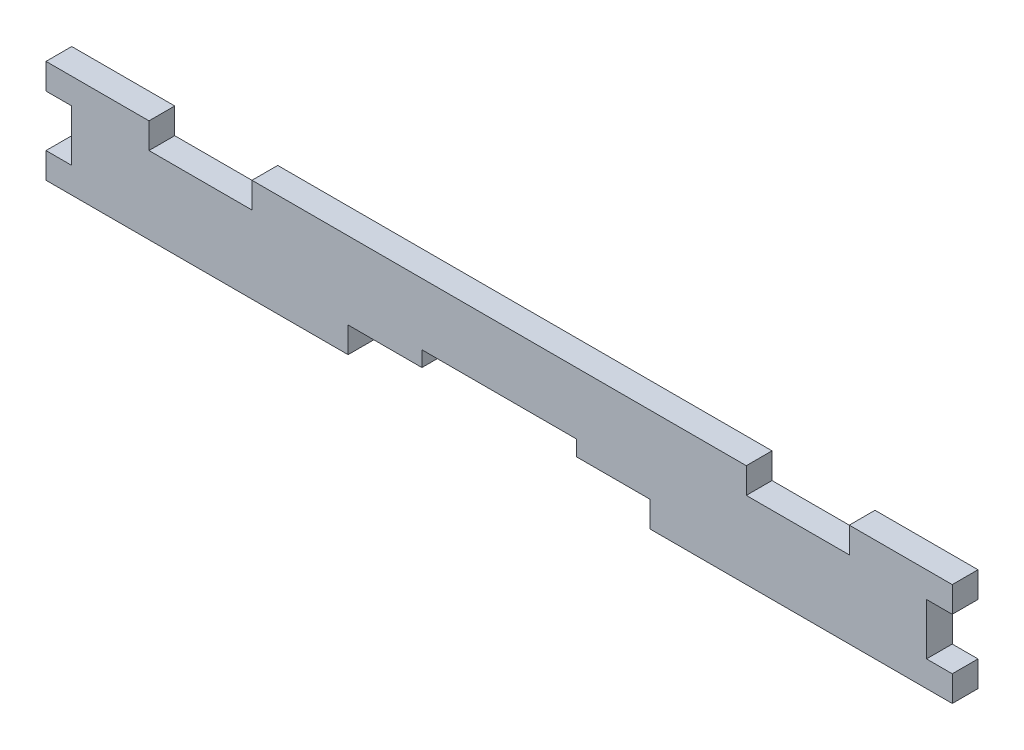
SolidWorks part; units mm, degrees
ref_plane "Alzado" through (0, 0, 0) normal (0, 0, 1) x (1, 0, 0)
ref_plane "Planta" through (0, 0, 0) normal (0, 1, 0) x (1, 0, 0)
ref_plane "Vista lateral" through (0, 0, 0) normal (1, 0, 0) x (0, 0, -1)
sketch "Croquis1" plane through (0, 0, 0) normal (0, 0, 1) x (1, 0, 0)
  line L0 (117.3333, 0) -> (176, 0)
  line L1 (0, 0) -> (58.6667, 0)
  line L2 (0, 0) -> (0, 5)
  line L3 (0, 20) -> (20, 20)
  line L4 (176, 0) -> (176, 5)
  line L6 (58.6667, 0) -> (58.6667, 5)
  line L7 (58.6667, 5) -> (117.3333, 5)
  line L8 (117.3333, 0) -> (117.3333, 5)
  line L9 (88, 15) -> (88, 10) construction
  line L10 (0, 15) -> (5, 15)
  line L12 (0, 5) -> (5, 5)
  line L13 (5, 15) -> (5, 5)
  line L14 (0, 15) -> (0, 20)
  line L15 (176, 15) -> (171, 15)
  line L16 (171, 15) -> (171, 5)
  line L17 (176, 5) -> (171, 5)
  line L18 (176, 15) -> (176, 20)
  line L19 (136, 20) -> (136, 15)
  line L25 (20, 20) -> (20, 15)
  line L26 (20, 15) -> (40, 15)
  line L27 (40, 20) -> (40, 15)
  line L28 (156, 15) -> (136, 15)
  line L29 (156, 20) -> (156, 15)
  line L30 (40, 20) -> (136, 20)
  line L31 (156, 20) -> (176, 20)
  dimension "D1" = 176
  dimension "D2" = 20
  dimension "D3" = 58.6667
  dimension "D4" = 58.6667
  dimension "D5" = 5
  dimension "D6" = 10
  dimension "D7" = 5
  dimension "D8" = 5
  dimension "D9" = 5
  dimension "D10" = 20
  dimension "D11" = 20
extrude "Saliente-Extruir1" add sketch "Croquis1" along normal blind 5
sketch "Croquis2" plane through (0, 0, 5) normal (0, 0, 1) x (1, 0, 0)
  line L0 (58.6667, 5) -> (117.3333, 5) construction
  line L5 (73.0017, 5) -> (103.0017, 5)
  line L6 (73.0017, 5) -> (73.0017, 8)
  line L7 (73.0017, 8) -> (103.0017, 8)
  line L8 (103.0017, 5) -> (103.0017, 8)
  line L9 (58.6667, 0) -> (58.6667, 5) construction
  dimension "D1" = 30
  dimension "D2" = 3
  dimension "D3" = 14.335
extrude "Cortar-Extruir1" cut sketch "Croquis2" against normal blind 10
sketch "Croquis3" plane through (0, 0, 5) normal (0, 0, 1) x (1, 0, 0)
  line L28 (58.6667, 5) -> (73.0017, 5)
  line L29 (73.0017, 5) -> (73.0017, 8)
  line L30 (73.0017, 8) -> (103.0017, 8)
  line L31 (103.0017, 8) -> (103.0017, 5)
  line L32 (103.0017, 5) -> (117.3333, 5)
  line L33 (117.3333, 5) -> (117.3333, 0)
  line L34 (117.3333, 0) -> (176, 0)
  line L35 (176, 0) -> (176, 5)
  line L36 (176, 5) -> (171, 5)
  line L37 (171, 5) -> (171, 15)
  line L38 (171, 15) -> (176, 15)
  line L39 (176, 15) -> (176, 20)
  line L40 (176, 20) -> (156, 20)
  line L41 (156, 20) -> (156, 15)
  line L42 (156, 15) -> (136, 15)
  line L43 (136, 15) -> (136, 20)
  line L44 (136, 20) -> (40, 20)
  line L45 (40, 20) -> (40, 15)
  line L46 (40, 15) -> (20, 15)
  line L47 (20, 15) -> (20, 20)
  line L48 (20, 20) -> (0, 20)
  line L49 (0, 20) -> (0, 15)
  line L50 (0, 15) -> (5, 15)
  line L51 (5, 15) -> (5, 5)
  line L52 (5, 5) -> (0, 5)
  line L53 (0, 5) -> (0, 0)
  line L54 (0, 0) -> (58.6667, 0)
  line L55 (58.6667, 0) -> (58.6667, 5)
  line L56 (58.6667, 5) -> (73.0017, 5)
  line L57 (73.0017, 5) -> (73.0017, 8)
  line L58 (73.0017, 8) -> (103.0017, 8)
  line L59 (103.0017, 8) -> (103.0017, 5)
  line L60 (103.0017, 5) -> (117.3333, 5)
  line L61 (117.3333, 5) -> (117.3333, 0)
  line L62 (117.3333, 0) -> (176, 0)
  line L63 (176, 0) -> (176, 5)
  line L64 (176, 5) -> (171, 5)
  line L65 (171, 5) -> (171, 15)
  line L66 (171, 15) -> (176, 15)
  line L67 (176, 15) -> (176, 20)
  line L68 (176, 20) -> (156, 20)
  line L69 (156, 20) -> (156, 15)
  line L70 (156, 15) -> (136, 15)
  line L71 (136, 15) -> (136, 20)
  line L72 (136, 20) -> (40, 20)
  line L73 (40, 20) -> (40, 15)
  line L74 (40, 15) -> (20, 15)
  line L75 (20, 15) -> (20, 20)
  line L76 (20, 20) -> (0, 20)
  line L77 (0, 20) -> (0, 15)
  line L78 (0, 15) -> (5, 15)
  line L79 (5, 15) -> (5, 5)
  line L80 (5, 5) -> (0, 5)
  line L81 (0, 5) -> (0, 0)
  line L82 (0, 0) -> (58.6667, 0)
  line L83 (58.6667, 0) -> (58.6667, 5)
  dimension "D1" = 0
